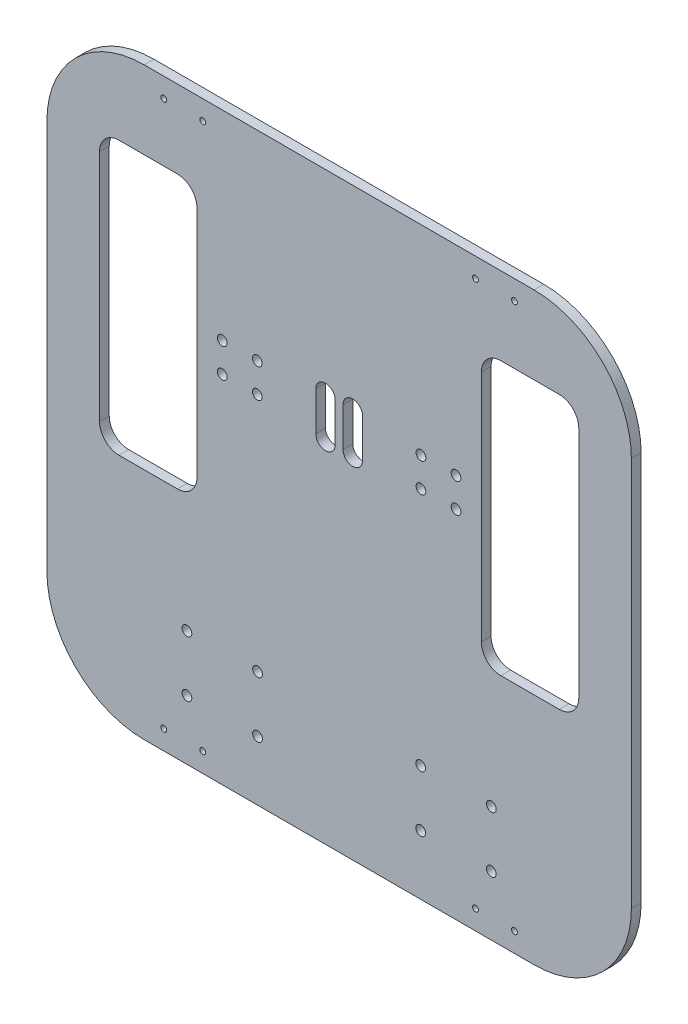
SolidWorks part; units mm, degrees
ref_plane "Front Plane" through (0, 0, 0) normal (0, 0, 1) x (1, 0, 0)
ref_plane "Top Plane" through (0, 0, 0) normal (0, 1, 0) x (1, 0, 0)
ref_plane "Right Plane" through (0, 0, 0) normal (1, 0, 0) x (0, 0, -1)
sketch "Sketch1" plane through (0, 0, 0) normal (0, 0, 1) x (1, 0, 0)
  line L0 (0, 0) -> (0, 150) construction
  line L4 (-60, 47.5) -> (-60, 32.5) construction
  line L5 (-42, 32.5) -> (-60, 32.5) construction
  line L6 (-42, 47.5) -> (-42, 32.5) construction
  line L7 (-42, 47.5) -> (-60, 47.5) construction
  line L8 (150, -150) -> (150, 150)
  line L9 (-150, -150) -> (150, -150)
  line L10 (-150, 150) -> (-150, -150)
  line L11 (150, 150) -> (-150, 150)
  line L17 (42, 47.5) -> (60, 47.5) construction
  line L18 (42, 47.5) -> (42, 32.5) construction
  line L19 (42, 32.5) -> (60, 32.5) construction
  line L20 (60, 47.5) -> (60, 32.5) construction
  line L21 (123, 110) -> (73, 110)
  line L22 (123, 110) -> (123, -30)
  line L23 (123, -30) -> (73, -30)
  line L24 (73, 110) -> (73, -30)
  line L25 (-73, 110) -> (-73, -30)
  line L26 (-123, -30) -> (-73, -30)
  line L27 (-123, 110) -> (-123, -30)
  line L28 (-123, 110) -> (-73, 110)
  line L29 (-60, 47.5) -> (-60, 32.5) construction
  line L30 (-70, 47.5) -> (-70, 32.5) construction
  line L31 (50, 47.5) -> (50, 32.5) construction
  line L32 (-50, 47.5) -> (-50, 32.5) construction
  line L33 (70, 47.5) -> (70, 32.5) construction
  circle A0 centre (42, 47.5) radius 2.5
  circle A1 centre (42, 32.5) radius 2.5
  circle A4 centre (60, 32.5) radius 2.5
  circle A5 centre (60, 47.5) radius 2.5
  circle A6 centre (-60, 47.5) radius 2.5
  circle A7 centre (-60, 32.5) radius 2.5
  circle A8 centre (-42, 32.5) radius 2.5
  circle A9 centre (-42, 47.5) radius 2.5
  point P3 (0, 150)
  point P4 (-150, 0)
  point P30 (42, 40)
  point P32 (73, 40)
  dimension "D8" = 5
  dimension "D11" = 18
  dimension "D3" = 300
  dimension "D4" = 10
  dimension "D5" = 10
  dimension "D7" = 15
  dimension "D9" = 81
  dimension "D10" = 100
  dimension "D12" = 50
  dimension "D13" = 140
  dimension "D16" = 40
  dimension "D2" = 300
extrude "Boss-Extrude1" add sketch "Sketch1" along normal blind 5
sketch "Sketch2" plane through (0, 0, 5) normal (0, 0, 1) x (1, 0, 0)
  line L0 (-60, 32.5) -> (-60, -150) construction
  line L1 (-150, -150) -> (150, -150) construction
  line L2 (0, 0) -> (0, -150) construction
  line L3 (-78.125, -119.4) -> (-41.875, -119.4) construction
  line L4 (-78.125, -119.4) -> (-78.125, -90.6) construction
  line L5 (-78.125, -90.6) -> (-41.875, -90.6) construction
  line L6 (-41.875, -119.4) -> (-41.875, -90.6) construction
  line L7 (-78.125, -119.4) -> (-41.875, -90.6) construction
  line L8 (-78.125, -90.6) -> (-41.875, -119.4) construction
  line L9 (78.125, -90.6) -> (41.875, -119.4) construction
  line L10 (78.125, -119.4) -> (41.875, -90.6) construction
  line L11 (41.875, -119.4) -> (41.875, -90.6) construction
  line L12 (78.125, -90.6) -> (41.875, -90.6) construction
  line L13 (78.125, -119.4) -> (78.125, -90.6) construction
  line L14 (78.125, -119.4) -> (41.875, -119.4) construction
  circle A0 centre (-60, 32.5) radius 2.5 construction
  circle A1 centre (-60, 32.5) radius 2.5
  circle A2 centre (-60, -105) radius 35 construction
  circle A3 centre (-78.125, -90.6) radius 2.5
  circle A4 centre (-41.875, -90.6) radius 2.5
  circle A5 centre (-41.875, -119.4) radius 2.5
  circle A6 centre (-78.125, -119.4) radius 2.5
  circle A9 centre (60, -105) radius 35 construction
  circle A12 centre (78.125, -119.4) radius 2.5
  circle A13 centre (41.875, -119.4) radius 2.5
  circle A14 centre (41.875, -90.6) radius 2.5
  circle A15 centre (78.125, -90.6) radius 2.5
  point P23 (0, 0)
  dimension "D1" = 70
  dimension "D5" = 5
  dimension "D2" = 10
  dimension "D3" = 28.8
  dimension "D4" = 36.25
extrude "Cut-Extrude1" cut sketch "Sketch2" against normal up to next (5 mm away)
fillet "Fillet1" radius 10 8 edges at (-123, -30, 2.5) (-73, -30, 2.5) (123, -30, 2.5) (73, -30, 2.5) (-123, 110, 2.5) (-73, 110, 2.5) (123, 110, 2.5) (73, 110, 2.5)
fillet "Fillet2" radius 50 4 edges at (-150, -150, 2.5) (150, -150, 2.5) (150, 150, 2.5) (-150, 150, 2.5)
sketch "Sketch3" plane through (0, 0, 5) normal (0, 0, 1) x (1, 0, 0)
  line L0 (0, 0) -> (0, 150) construction
  line L1 (-42, 30) -> (42, 30) construction
  line L2 (-42, 30) -> (-42, 50) construction
  line L3 (-42, 50) -> (42, 50) construction
  line L4 (42, 30) -> (42, 50) construction
  line L5 (-12, 30) -> (-2, 30)
  line L6 (-12, 30) -> (-12, 50)
  line L7 (-12, 50) -> (-2, 50)
  line L8 (-2, 30) -> (-2, 50)
  line L9 (100, 150) -> (-100, 150) construction
  line L10 (2, 30) -> (2, 50)
  line L11 (12, 30) -> (12, 50)
  circle A0 centre (-42, 32.5) radius 2.5 construction
  circle A1 centre (42, 47.5) radius 2.5 construction
  circle A2 centre (-42, 47.5) radius 2.5 construction
  arc A3 (-12, 30) -> (-2, 30) centre (-7, 30) ccw
  arc A4 (-12, 50) -> (-2, 50) centre (-7, 50) cw
  arc A5 (12, 50) -> (2, 50) centre (7, 50) ccw
  arc A6 (12, 30) -> (2, 30) centre (7, 30) cw
  point P19 (-42, 40)
  dimension "D1" = 30
  dimension "D2" = 10
extrude "Cut-Extrude2" cut sketch "Sketch3" against normal through all contours L5 L8 L7 L6 | A4 L7 | L5 A3 | A6 L11 A5 L10
sketch "Sketch4" plane through (0, 0, 5) normal (0, 0, 1) x (1, 0, 0)
  line L0 (0, 0) -> (-150, 0) construction
  line L1 (-150, 100) -> (-150, -100) construction
  line L2 (100, -140) -> (-100, -140) construction
  line L8 (-100, 150) -> (-100, -150) construction
  line L9 (100, 150) -> (100, -150) construction
  line L10 (90, 150) -> (90, -150) construction
  line L11 (-90, 150) -> (-90, -150) construction
  line L12 (-140, 100) -> (-140, -100)
  line L13 (-100, -140) -> (100, -140)
  line L14 (140, -100) -> (140, 100)
  line L15 (100, 140) -> (-100, 140)
  line L16 (-140, 100) -> (-140, -100) construction
  line L17 (-100, -140) -> (100, -140) construction
  line L18 (140, -100) -> (140, 100) construction
  line L19 (100, 140) -> (-100, 140) construction
  circle A0 centre (-70, -140) radius 1.5
  circle A1 centre (70, -140) radius 1.5
  circle A2 centre (-90, -140) radius 1.5
  circle A3 centre (90, -140) radius 1.5
  circle A8 centre (90, 140) radius 1.5
  circle A9 centre (-90, 140) radius 1.5
  circle A10 centre (70, 140) radius 1.5
  circle A11 centre (-70, 140) radius 1.5
  arc A12 (-140, -100) -> (-100, -140) centre (-100, -100) ccw
  arc A13 (100, -140) -> (140, -100) centre (100, -100) ccw
  arc A14 (140, 100) -> (100, 140) centre (100, 100) ccw
  arc A15 (-100, 140) -> (-140, 100) centre (-100, 100) ccw
  arc A16 (-140, -100) -> (-100, -140) centre (-100, -100) ccw construction
  arc A17 (100, -140) -> (140, -100) centre (100, -100) ccw construction
  arc A18 (140, 100) -> (100, 140) centre (100, 100) ccw construction
  arc A19 (-100, 140) -> (-140, 100) centre (-100, 100) ccw construction
  dimension "D4" = 3
  dimension "D5" = 3
  dimension "D6" = 20
  dimension "D7" = 20
  dimension "D1" = 10
  dimension "D2" = 10
  dimension "D3" = 10
extrude "Cut-Extrude3" cut sketch "Sketch4" against normal up to next
